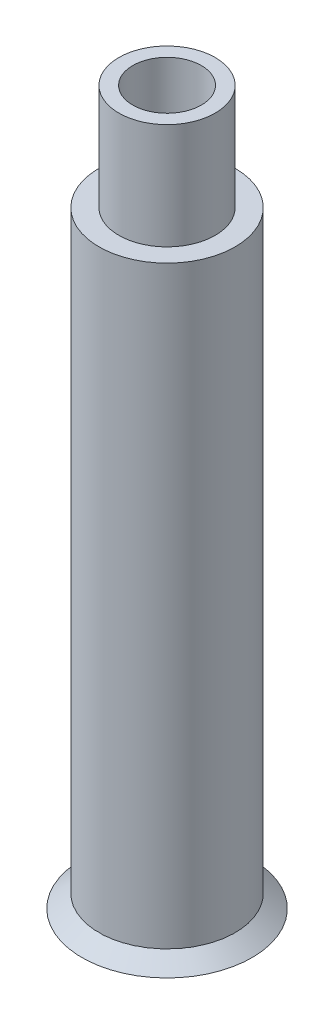
SolidWorks part; units mm, degrees
ref_plane "Front Plane" through (0, 0, 0) normal (0, 0, 1) x (1, 0, 0)
ref_plane "Top Plane" through (0, 0, 0) normal (0, 1, 0) x (1, 0, 0)
ref_plane "Right Plane" through (0, 0, 0) normal (1, 0, 0) x (0, 0, -1)
sketch "Sketch1" plane through (0, 0, 0) normal (0, 1, 0) x (1, 0, 0)
  circle A0 centre (0, 0) radius 6.35
  dimension "D1" = 12.7
extrude "Boss-Extrude1" add sketch "Sketch1" along normal blind 56.642
sketch "Sketch2" plane through (0, 0, 0) normal (1, 0, 0) x (0, 0, -1)
  line L0 (-3.2004, 2.2749) -> (-4.1735, 2.2749)
  line L1 (-4.1735, 2.2749) -> (-7.8359, 0)
  line L3 (-4.4958, 2.665) -> (-7.9375, 0)
  line L4 (-7.9375, 0) -> (-7.8359, 0)
  line L5 (-4.5223, 2.665) -> (-3.2004, 2.665)
  line L7 (-4.4958, 2.665) -> (-4.4958, 66.5239)
  line L8 (-4.4958, 66.5239) -> (-3.2004, 66.5239)
  line L9 (-3.2004, 66.5239) -> (-3.2004, 2.665)
  line L11 (-6.35, 0) -> (6.35, 0) construction
  line L13 (-3.2004, 2.2749) -> (-3.2004, 2.665)
  line L14 (0, 0) -> (0, 4.302)
  dimension "D1" = 4.4958
  dimension "D2" = 3.2004
  dimension "D3" = 0.1016
  dimension "D4" = 7.9375
  dimension "D5" = 63.8589
revolve "Revolve1" add sketch "Sketch2" angle 360 about L14
sketch "Sketch4" plane through (0, 66.5239, 0) normal (0, 1, 0) x (1, 0, 0)
  circle A0 centre (0, 0) radius 3.2004
  dimension "D1" = 6.4008
